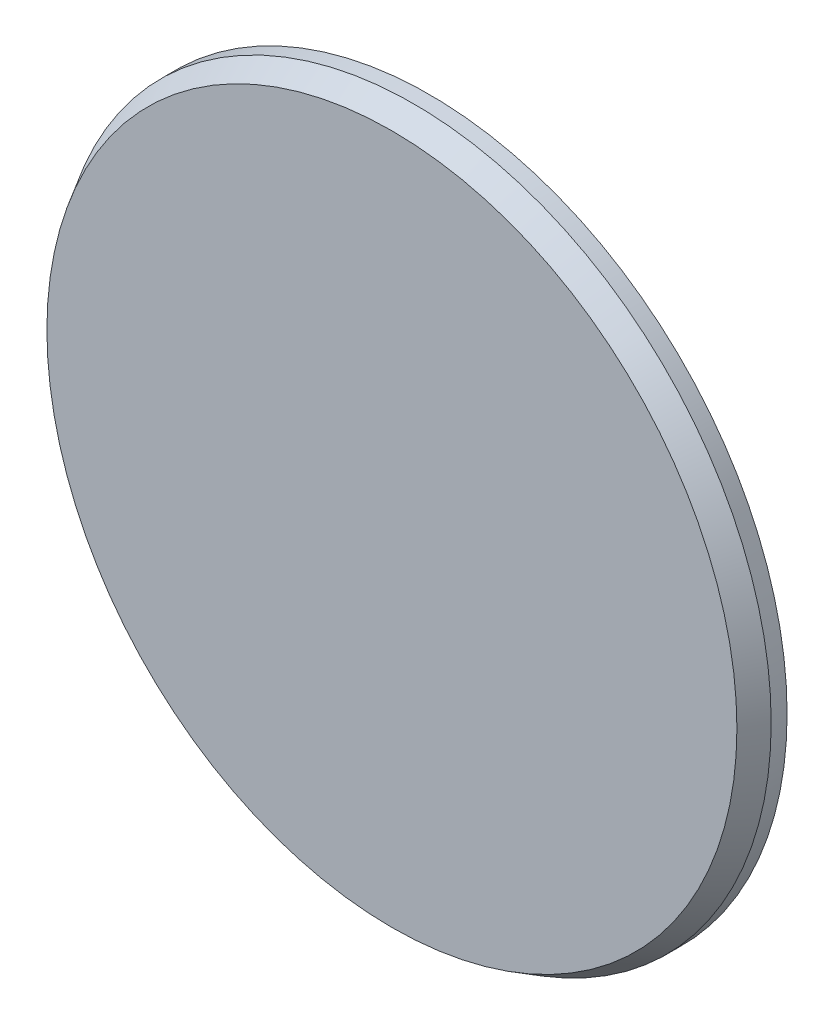
SolidWorks part; units mm, degrees
ref_plane "Front" through (0, 0, 0) normal (0, 0, 1) x (1, 0, 0)
ref_plane "Top" through (0, 0, 0) normal (0, 1, 0) x (1, 0, 0)
ref_plane "Right" through (0, 0, 0) normal (1, 0, 0) x (0, 0, -1)
sketch "Esquisse1" plane through (0, 0, 0) normal (0, 0, 1) x (1, 0, 0)
  circle A0 centre (0, 0) radius 28.5
  dimension "D1" = 57
extrude "Boss.-Extru.1" add sketch "Esquisse1" along normal blind 3
chamfer "Chanfrein1" distance 1 angle 60 1 edges at (28.5, 0, 3)
